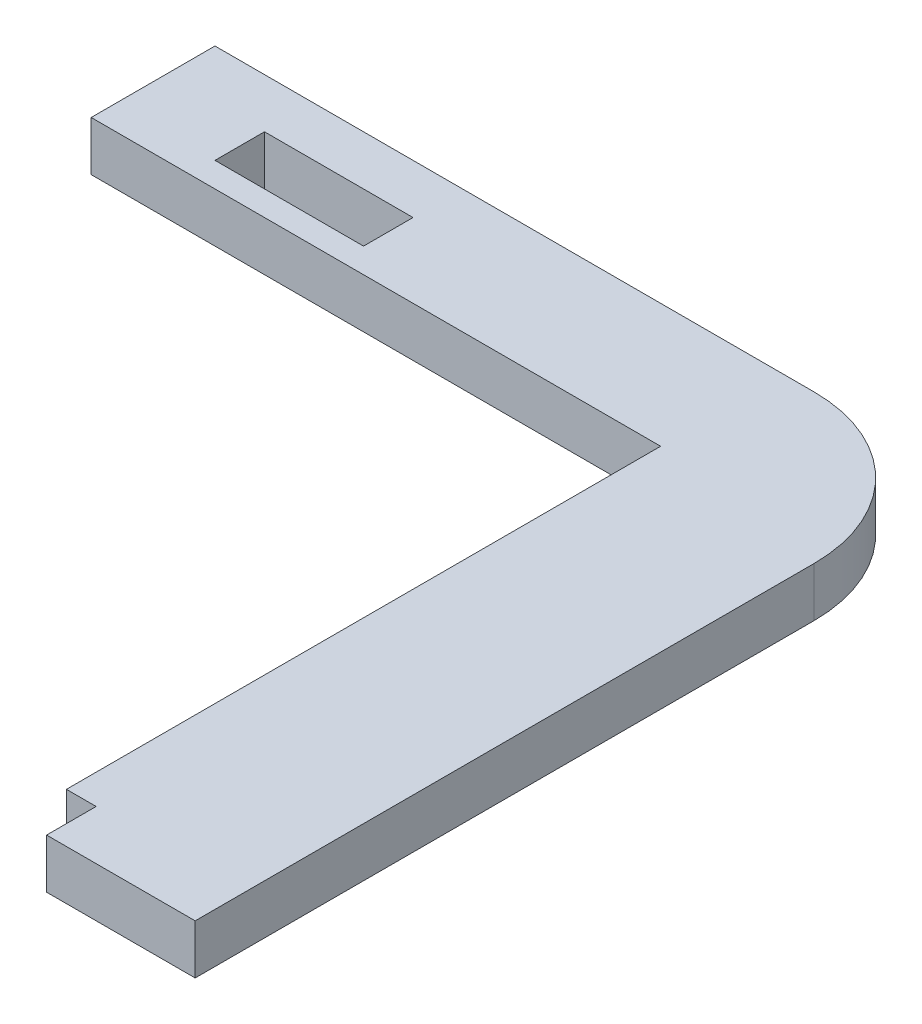
SolidWorks part; units mm, degrees
ref_plane "Front Plane" through (0, 0, 0) normal (0, 0, 1) x (1, 0, 0)
ref_plane "Top Plane" through (0, 0, 0) normal (0, 1, 0) x (1, 0, 0)
ref_plane "Right Plane" through (0, 0, 0) normal (1, 0, 0) x (0, 0, -1)
sketch "Sketch1" plane through (0, 0, 0) normal (0, 1, 0) x (1, 0, 0)
  line L0 (-26.5, -22.5) -> (-29.5, -22.5)
  line L4 (-29.5, -22.5) -> (-29.5, 37.5)
  line L6 (-26.5, -22.5) -> (-26.5, -27.5)
  line L7 (-26.5, -27.5) -> (-11.5, -27.5)
  line L9 (-11.5, 50) -> (-87, 50)
  line L11 (-29.5, 37.5) -> (-87, 37.5)
  line L12 (-87, 50) -> (-87, 37.5)
  line L13 (-77, 40) -> (-62, 40)
  line L14 (-77, 40) -> (-77, 45)
  line L15 (-77, 45) -> (-62, 45)
  line L16 (-62, 40) -> (-62, 45)
  line L17 (-11.5, 50) -> (-11.5, -27.5)
  point P12 (-87, 43.75)
  dimension "D2" = 3
  dimension "D3" = 15
  dimension "D4" = 60
  dimension "D5" = 12.5
  dimension "D6" = 57.5
  dimension "D7" = 10
  dimension "D8" = 2.5
  dimension "D9" = 5
  dimension "D10" = 15
  dimension "D11" = 5
extrude "Boss-Extrude1" add sketch "Sketch1" along normal blind 5
fillet "Fillet3" radius 15 1 edges at (-11.5, 2.5, -50)
